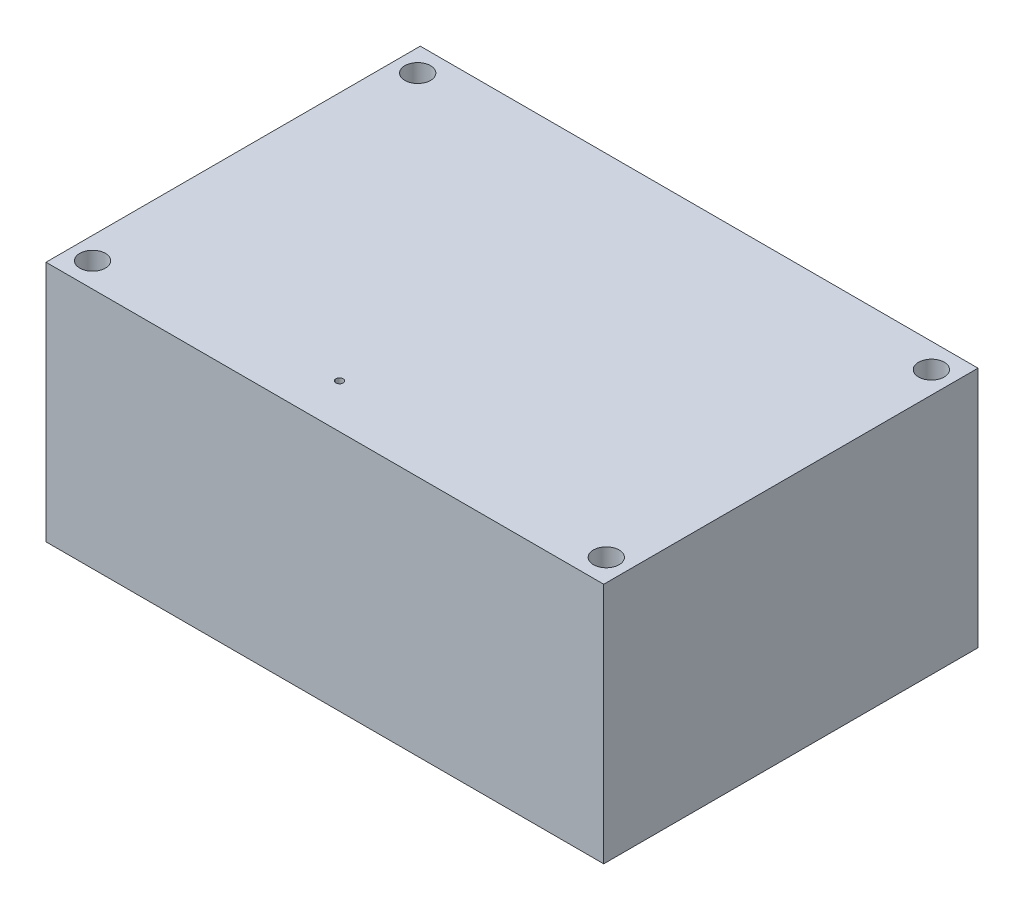
SolidWorks part; units mm, degrees
ref_plane "Front Plane" through (0, 0, 0) normal (0, 0, 1) x (1, 0, 0)
ref_plane "Top Plane" through (0, 0, 0) normal (0, 1, 0) x (1, 0, 0)
ref_plane "Right Plane" through (0, 0, 0) normal (1, 0, 0) x (0, 0, -1)
sketch "Sketch1" plane through (0, 0, 0) normal (0, 1, 0) x (1, 0, 0)
  line L1 (-38, -25.5) -> (38, -25.5)
  line L2 (-38, -25.5) -> (-38, 25.5)
  line L3 (-38, 25.5) -> (38, 25.5)
  line L4 (38, -25.5) -> (38, 25.5)
  line L5 (-38, -25.5) -> (38, 25.5) construction
  line L6 (-38, 25.5) -> (38, -25.5) construction
  point P0 (0, 0)
  dimension "D1" = 51
  dimension "D2" = 76
extrude "Boss-Extrude1" add sketch "Sketch1" along normal blind 33
sketch "Sketch2" plane through (0, 0, 0) normal (0, 1, 0) x (1, 0, 0)
  line L1 (-35, -22.15) -> (35, -22.15) construction
  line L2 (-35, -22.15) -> (-35, 22.15) construction
  line L3 (-35, 22.15) -> (35, 22.15) construction
  line L4 (35, -22.15) -> (35, 22.15) construction
  line L5 (-35, -22.15) -> (35, 22.15) construction
  line L6 (-35, 22.15) -> (35, -22.15) construction
  circle A0 centre (-35, 22.15) radius 1.75
  circle A1 centre (35, 22.15) radius 1.75
  circle A2 centre (35, -22.15) radius 1.75
  circle A3 centre (-35, -22.15) radius 1.75
  point P0 (0, 0)
  dimension "D3" = 3.5
  dimension "D1" = 44.3
  dimension "D2" = 70
extrude "Cut-Extrude1" cut sketch "Sketch2" along normal through all
sketch "Sketch3" plane through (0, 33, 0) normal (0, 1, 0) x (1, 0, 0)
  line L0 (-38, 25.5) -> (-38, -25.5) construction
  line L1 (-38, -25.5) -> (38, -25.5) construction
  circle A0 centre (-4, -19.5) radius 0.5
  point P0 (-4, -19.5)
  dimension "D3" = 1
  dimension "D1" = 34
  dimension "D2" = 6
extrude "IMU_center_location" cut sketch "Sketch3" against normal blind 5
